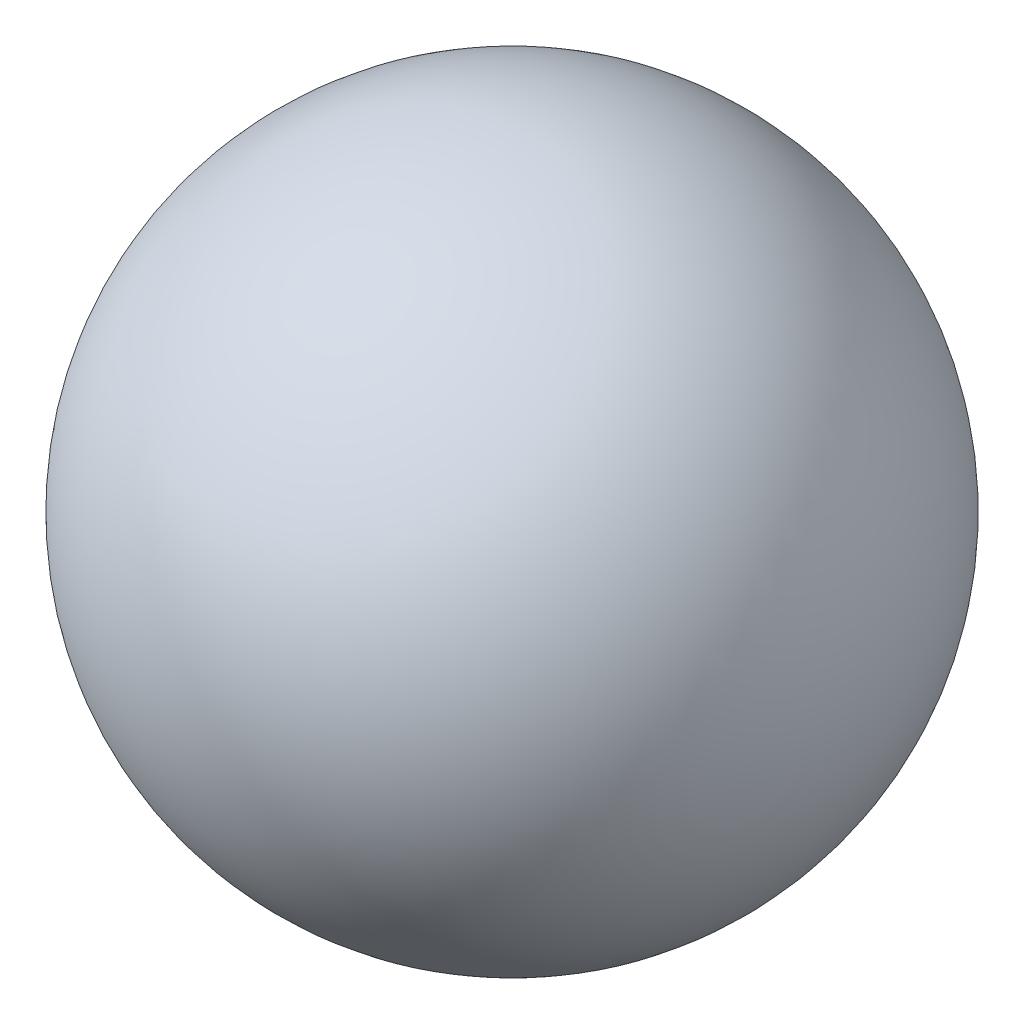
SolidWorks part; units mm, degrees
ref_plane "前视基准面" through (0, 0, 0) normal (0, 0, 1) x (1, 0, 0)
ref_plane "上视基准面" through (0, 0, 0) normal (0, 1, 0) x (1, 0, 0)
ref_plane "右视基准面" through (0, 0, 0) normal (1, 0, 0) x (0, 0, -1)
other "Configuration Table"
sketch "草图1" plane through (0, 0, 0) normal (0, 0, 1) x (1, 0, 0)
  line L0 (0, 95) -> (0, -95) construction
  line L1 (0, 95) -> (0, -95)
  arc A0 (0, -95) -> (0, 95) centre (0, 0) ccw
  dimension "D1" = 190
revolve "旋转1" add sketch "草图1" angle 360 about L0
